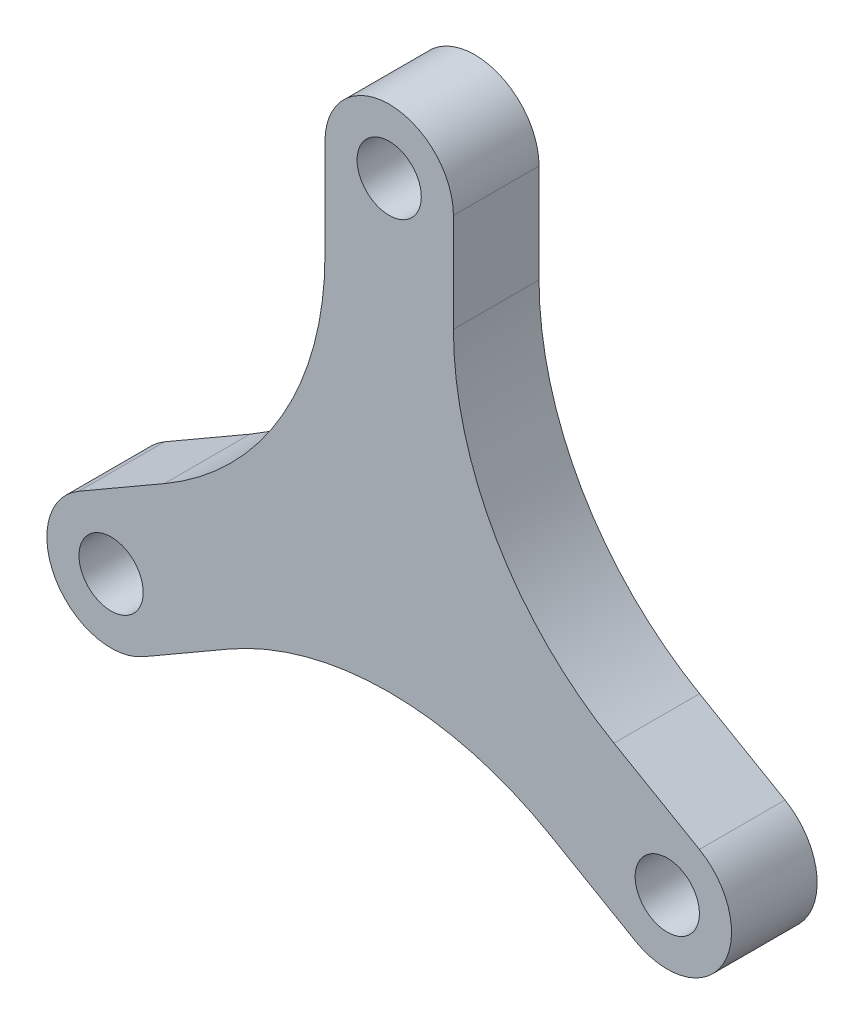
SolidWorks part; units mm, degrees
material "PMMA"
ref_plane "前视基准面" through (0, 0, 0) normal (0, 0, 1) x (1, 0, 0)
ref_plane "上视基准面" through (0, 0, 0) normal (0, 1, 0) x (1, 0, 0)
ref_plane "右视基准面" through (0, 0, 0) normal (1, 0, 0) x (0, 0, -1)
other "Configuration Table"
sketch "草图1" plane through (0, 0, 0) normal (0, 0, 1) x (1, 0, 0)
  line L0 (0, 15) -> (0, 0) construction
  line L1 (0, 0) -> (-12.9904, -7.5) construction
  line L2 (0, 0) -> (12.9904, -7.5) construction
  line L3 (-3, 15) -> (-3, 1.7321)
  line L4 (3, 15) -> (3, 1.7321)
  line L5 (14.4904, -4.9019) -> (3, 1.7321)
  line L6 (11.4904, -10.0981) -> (0, -3.4641)
  line L7 (-11.4904, -10.0981) -> (0, -3.4641)
  line L8 (-14.4904, -4.9019) -> (-3, 1.7321)
  circle A0 centre (0, 0) radius 15 construction
  arc A1 (3, 15) -> (-3, 15) centre (0, 15) ccw
  circle A4 centre (0, 15) radius 1.5
  arc A5 (11.4904, -10.0981) -> (14.4904, -4.9019) centre (12.9904, -7.5) ccw
  circle A6 centre (12.9904, -7.5) radius 1.5
  arc A7 (-14.4904, -4.9019) -> (-11.4904, -10.0981) centre (-12.9904, -7.5) ccw
  circle A8 centre (-12.9904, -7.5) radius 1.5
  point P26 (0, 0)
  dimension "D3" = 30
  dimension "D4" = 3
  dimension "D5" = 6
  dimension "D1" = 120
  dimension "D2" = 120
  dimension "D6" = 3
extrude "凸台-拉伸1" add sketch "草图1" along normal blind 4
fillet "圆角1" radius 15 3 edges at (0, -3.4641, 2) (-3, 1.7321, 2) (3, 1.7321, 2)
